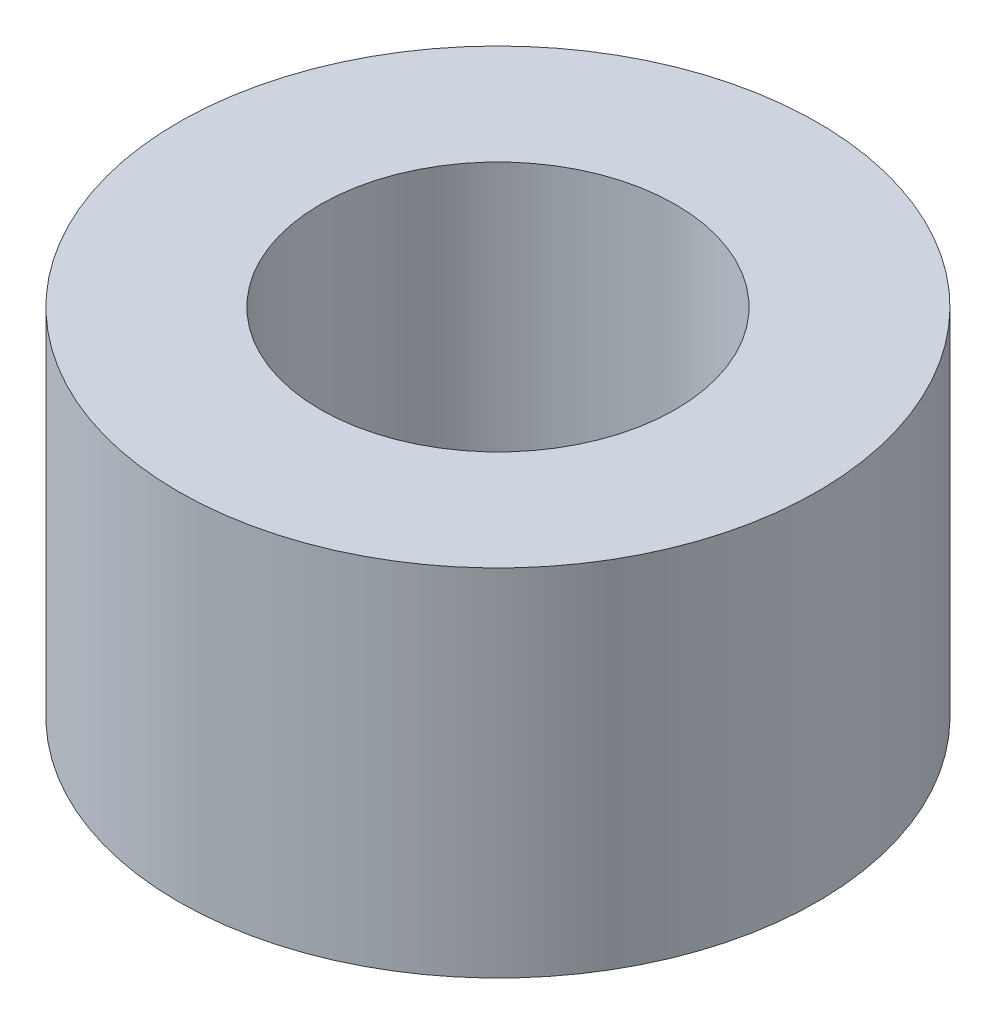
SolidWorks part; units mm, degrees
ref_plane "Front Plane" through (0, 0, 0) normal (0, 0, 1) x (1, 0, 0)
ref_plane "Top Plane" through (0, 0, 0) normal (0, 1, 0) x (1, 0, 0)
ref_plane "Right Plane" through (0, 0, 0) normal (1, 0, 0) x (0, 0, -1)
sketch "Sketch1" plane through (0, 0, 0) normal (0, 0, 1) x (1, 0, 0)
  line L0 (0, 9.4091) -> (0, -5.8636) construction
  line L2 (-2.5, -2.5) -> (-4.5, -2.5)
  line L3 (-2.5, -2.5) -> (-2.5, 2.5)
  line L4 (-2.5, 2.5) -> (-4.5, 2.5)
  line L5 (-4.5, -2.5) -> (-4.5, 2.5)
  line L6 (-2.5, -2.5) -> (-4.5, 2.5) construction
  line L7 (-2.5, 2.5) -> (-4.5, -2.5) construction
  point P3 (-3.5, 0)
  point P8 (0, 0)
  dimension "D1" = 2
  dimension "D2" = 5
  dimension "D3" = 2.5
revolve "Revolve1" add sketch "Sketch1" angle 360 about L0
